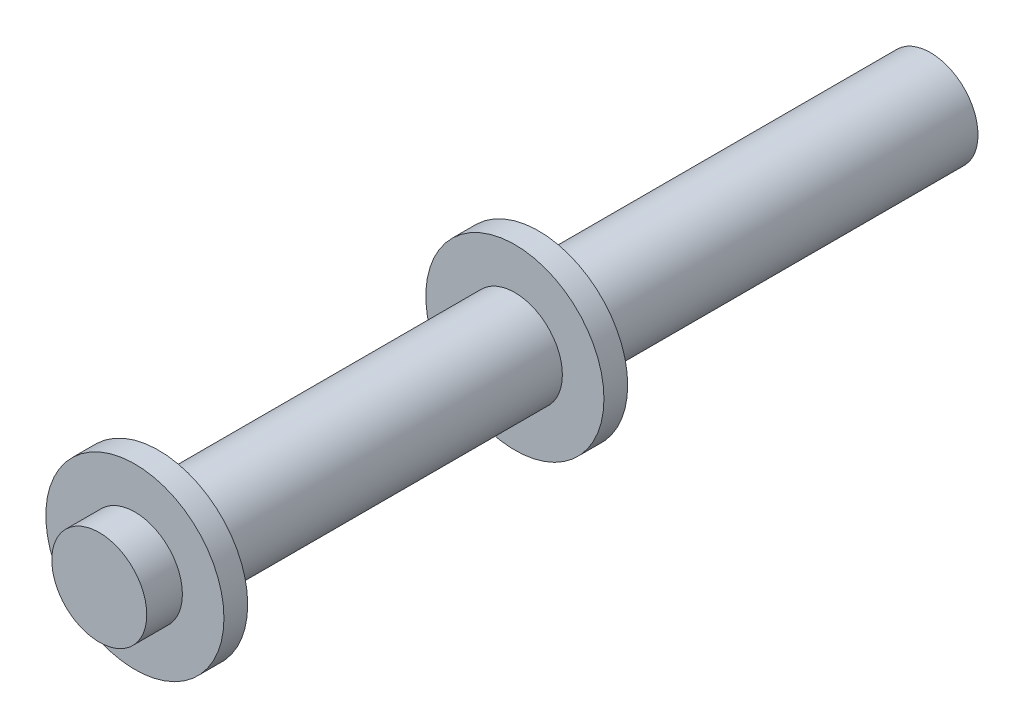
SolidWorks part; units mm, degrees
material "Plain Carbon Steel"
ref_plane "Front Plane" through (0, 0, 0) normal (0, 0, 1) x (1, 0, 0)
ref_plane "Top Plane" through (0, 0, 0) normal (0, 1, 0) x (1, 0, 0)
ref_plane "Right Plane" through (0, 0, 0) normal (1, 0, 0) x (0, 0, -1)
sketch "Sketch1" plane through (0, 0, 0) normal (0, 0, 1) x (1, 0, 0)
  circle A0 centre (0, 0) radius 10.16
  dimension "D1" = 20.32
extrude "Boss-Extrude1" add sketch "Sketch1" along normal blind 177.8
sketch "Sketch2" plane through (0, 0, 177.8) normal (0, 0, 1) x (1, 0, 0)
  circle A0 centre (0, 0) radius 19.05
  dimension "D1" = 38.1
extrude "Boss-Extrude2" add sketch "Sketch2" along normal blind 5.08 from offset 12.7 contours A0 offset against normal yes
sketch "Sketch3" plane through (0, 0, 177.8) normal (0, 0, 1) x (1, 0, 0)
  circle A0 centre (0, 0) radius 19.05
  dimension "D1" = 38.1
extrude "Boss-Extrude3" add sketch "Sketch3" against normal blind 5.08 from offset 88.9
